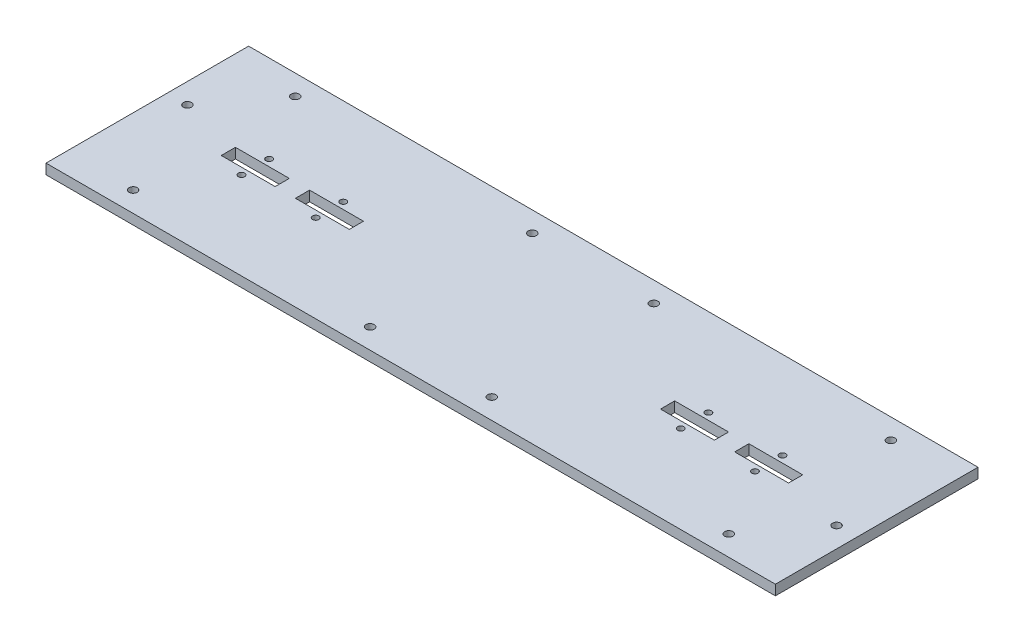
SolidWorks part; units mm, degrees
ref_plane "Front Plane" through (0, 0, 0) normal (0, 0, 1) x (1, 0, 0)
ref_plane "Top Plane" through (0, 0, 0) normal (0, 1, 0) x (1, 0, 0)
ref_plane "Right Plane" through (0, 0, 0) normal (1, 0, 0) x (0, 0, -1)
sketch "Sketch1" plane through (0, 0, 0) normal (0, 1, 0) x (1, 0, 0)
  line L0 (228.6, 127) -> (228.6, 0) construction
  line L1 (0, 0) -> (457.2, 0)
  line L2 (0, 0) -> (0, 127)
  line L3 (0, 127) -> (457.2, 127)
  line L4 (457.2, 0) -> (457.2, 127)
  line L6 (444.5, 12.7) -> (12.7, 12.7) construction
  line L7 (444.5, 12.7) -> (444.5, 114.3) construction
  line L8 (444.5, 114.3) -> (12.7, 114.3) construction
  line L9 (12.7, 12.7) -> (12.7, 114.3) construction
  line L10 (444.5, 12.7) -> (12.7, 114.3) construction
  line L11 (444.5, 114.3) -> (12.7, 12.7) construction
  circle A0 centre (41.91, 114.3) radius 2.5527
  circle A1 centre (415.29, 114.3) radius 2.5527
  circle A2 centre (415.29, 12.7) radius 2.5527
  circle A3 centre (41.91, 12.7) radius 2.5527
  circle A4 centre (190.5, 114.3) radius 2.5527
  circle A5 centre (266.7, 114.3) radius 2.5527
  circle A6 centre (190.5, 12.7) radius 2.5527
  circle A8 centre (266.7, 12.7) radius 2.5527
  circle A9 centre (444.5, 51.054) radius 2.5527
  circle A11 centre (12.7, 75.946) radius 2.5527
  point P7 (228.6, 63.5)
  dimension "D5" = 5.1054
  dimension "D6" = 190.5
  dimension "D7" = 41.91
  dimension "D8" = 5.1054
  dimension "D9" = 190.5
  dimension "D10" = 41.91
  dimension "D11" = 190.5
  dimension "D13" = 5.1054
  dimension "D15" = 5.1054
  dimension "D18" = 5.1054
  dimension "D19" = 190.5
  dimension "D21" = 5.1054
  dimension "D23" = 5.1054
  dimension "D20" = 5.1054
  dimension "D24" = 5.1054
  dimension "D25" = 5.1054
  dimension "D1" = 457.2
  dimension "D2" = 127
  dimension "D3" = 12.7
  dimension "D4" = 12.7
  dimension "D14" = 41.91
  dimension "D16" = 41.91
  dimension "D17" = 51.054
  dimension "D22" = 51.054
extrude "Boss-Extrude1" add sketch "Sketch1" along normal blind 6.35
sketch "Sketch2" plane through (0, 0, 0) normal (0, -1, 0) x (-1, 0, 0)
  line L0 (0, 63.5) -> (-457.2, 63.5) construction
  line L1 (0, 127) -> (0, 0) construction
  line L2 (-457.2, 0) -> (-457.2, 127) construction
  line L3 (-389.509, 63.5) -> (-389.509, 39.2506) construction
  line L4 (-114.173, 63.5) -> (-114.173, 35.5001) construction
  line L5 (-131.064, 67.945) -> (-97.282, 67.945)
  line L6 (-131.064, 67.945) -> (-131.064, 59.055)
  line L7 (-131.064, 59.055) -> (-97.282, 59.055)
  line L8 (-97.282, 67.945) -> (-97.282, 59.055)
  line L9 (-131.064, 67.945) -> (-97.282, 59.055) construction
  line L10 (-406.4, 67.945) -> (-372.618, 67.945)
  line L11 (-406.4, 67.945) -> (-406.4, 59.055)
  line L12 (-406.4, 59.055) -> (-372.618, 59.055)
  line L13 (-372.618, 67.945) -> (-372.618, 59.055)
  line L14 (-406.4, 67.945) -> (-372.618, 59.055) construction
  line L15 (-406.4, 59.055) -> (-372.618, 67.945) construction
  line L16 (-389.509, 39.2506) -> (-389.509, 86.9922) construction
  line L17 (-343.027, 63.5) -> (-343.027, 39.2506) construction
  line L18 (-359.918, 67.945) -> (-326.136, 67.945)
  line L19 (-359.918, 67.945) -> (-359.918, 59.055)
  line L20 (-359.918, 59.055) -> (-326.136, 59.055)
  line L21 (-326.136, 67.945) -> (-326.136, 59.055)
  line L22 (-359.918, 67.945) -> (-326.136, 59.055) construction
  line L23 (-359.918, 59.055) -> (-326.136, 67.945) construction
  line L24 (-343.027, 39.2506) -> (-343.027, 86.9922) construction
  line L25 (-131.064, 59.055) -> (-97.282, 67.945) construction
  line L26 (-114.173, 35.5001) -> (-114.173, 83.2417) construction
  line L27 (-67.691, 63.5) -> (-67.691, 39.2506) construction
  line L28 (-84.582, 67.945) -> (-50.8, 67.945)
  line L29 (-84.582, 67.945) -> (-84.582, 59.055)
  line L30 (-84.582, 59.055) -> (-50.8, 59.055)
  line L31 (-50.8, 67.945) -> (-50.8, 59.055)
  line L32 (-84.582, 67.945) -> (-50.8, 59.055) construction
  line L33 (-84.582, 59.055) -> (-50.8, 67.945) construction
  line L34 (-67.691, 39.2506) -> (-67.691, 86.9922) construction
  line L35 (0, 127) -> (0, 0) construction
  circle A0 centre (-389.509, 54.864) radius 1.9812
  circle A1 centre (-389.509, 72.136) radius 1.9812
  circle A2 centre (-343.027, 54.864) radius 1.9812
  circle A3 centre (-343.027, 72.136) radius 1.9812
  circle A4 centre (-114.173, 54.864) radius 1.9812
  circle A5 centre (-114.173, 72.136) radius 1.9812
  circle A6 centre (-67.691, 54.864) radius 1.9812
  circle A7 centre (-67.691, 72.136) radius 1.9812
  point P6 (-114.173, 63.5)
  point P11 (-389.509, 63.5)
  point P23 (-343.027, 63.5)
  point P42 (-67.691, 63.5)
  dimension "D9" = 3.9624
  dimension "D10" = 3.9624
  dimension "D15" = 3.9624
  dimension "D16" = 3.9624
  dimension "D21" = 3.9624
  dimension "D22" = 3.9624
  dimension "D27" = 3.9624
  dimension "D28" = 3.9624
  dimension "D2" = 33.782
  dimension "D3" = 8.89
  dimension "D4" = 33.782
  dimension "D5" = 50.8
  dimension "D6" = 8.89
  dimension "D7" = 17.272
  dimension "D8" = 8.636
  dimension "D11" = 33.782
  dimension "D12" = 8.89
  dimension "D13" = 17.272
  dimension "D14" = 8.636
  dimension "D17" = 0
  dimension "D18" = 12.7
  dimension "D19" = 17.272
  dimension "D20" = 8.636
  dimension "D23" = 33.782
  dimension "D24" = 8.89
  dimension "D25" = 17.272
  dimension "D26" = 8.636
  dimension "D29" = 12.7
  dimension "D30" = 0
  dimension "D31" = 50.8
  dimension "D32" = 0
extrude "Cut-Extrude1" cut sketch "Sketch2" against normal up to next
